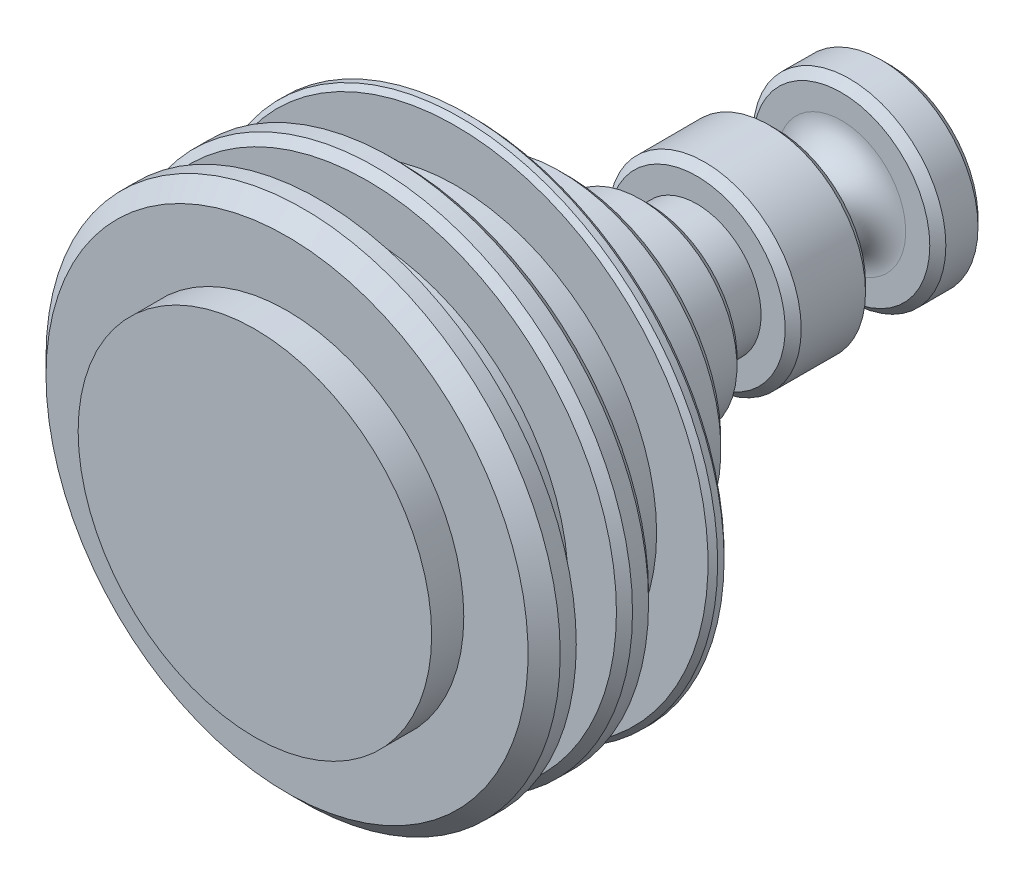
SolidWorks part; units mm, degrees
ref_plane "Plane1" through (0, 0, 0) normal (0, 0, 1) x (1, 0, 0)
ref_plane "Plane2" through (0, 0, 0) normal (0, 1, 0) x (1, 0, 0)
ref_plane "Plane3" through (0, 0, 0) normal (1, 0, 0) x (0, 0, -1)
sketch "Esquisse1" plane through (0, 0, 0) normal (0, 0, 1) x (1, 0, 0)
  circle A0 centre (0, 0) radius 11
  dimension "D1" = 22
extrude "fond" add sketch "Esquisse1" along normal blind 2
sketch "Esquisse2" plane through (0, 0, 0) normal (0, 0, -1) x (-1, 0, 0)
  circle A0 centre (0, 0) radius 16
  dimension "D1" = 32
extrude "cylindre 1" add sketch "Esquisse2" along normal blind 2
sketch "Esquisse3" plane through (0, 0, -2) normal (0, 0, -1) x (-1, 0, 0)
  circle A0 centre (0, 0) radius 12.5
  dimension "D1" = 25
extrude "cylindre 2" add sketch "Esquisse3" along normal blind 3
sketch "Esquisse4" plane through (0, 0, -5) normal (0, 0, -1) x (-1, 0, 0)
  circle A0 centre (0, 0) radius 16
  dimension "D1" = 32
extrude "cylindre 3" add sketch "Esquisse4" along normal blind 2
sketch "Esquisse5" plane through (0, 0, -7) normal (0, 0, -1) x (-1, 0, 0)
  circle A0 centre (0, 0) radius 12.5
  dimension "D1" = 25
extrude "cylindre 4" add sketch "Esquisse5" along normal blind 3.5
sketch "Esquisse6" plane through (0, 0, -10.5) normal (0, 0, -1) x (-1, 0, 0)
  circle A0 centre (0, 0) radius 16
  dimension "D1" = 32
extrude "cylindre 5" add sketch "Esquisse6" along normal blind 1
sketch "Esquisse7" plane through (0, 0, -11.5) normal (0, 0, -1) x (-1, 0, 0)
  circle A0 centre (0, 0) radius 10
  dimension "D1" = 20
extrude "cylindre 6" add sketch "Esquisse7" along normal blind 6
sketch "Esquisse8" plane through (0, 0, -17.5) normal (0, 0, -1) x (-1, 0, 0)
  circle A0 centre (0, 0) radius 6
  dimension "D1" = 12
extrude "cylindre 7" add sketch "Esquisse8" along normal blind 5
sketch "Esquisse9" plane through (0, 0, -22.5) normal (0, 0, -1) x (-1, 0, 0)
  circle A0 centre (0, 0) radius 4
  dimension "D1" = 8
extrude "cylindre 8" add sketch "Esquisse9" along normal blind 3
sketch "Esquisse12" plane through (0, 0, -25.5) normal (0, 0, -1) x (-1, 0, 0)
  circle A0 centre (0, 0) radius 6
  dimension "D1" = 12
extrude "cylindre 9" add sketch "Esquisse12" along normal blind 12
sketch "Esquisse13" plane through (0, 0, 0) normal (0, 1, 0) x (1, 0, 0)
  line L0 (-10.4858, 34.5) -> (-4, 34.5)
  line L1 (-10.4858, 30.5) -> (-4, 30.5)
  line L2 (-6, 25.5) -> (6, 25.5) construction
  line L3 (-6, 37.5) -> (-6, 25.5) construction
  line L5 (-10.4858, 30.5) -> (-10.4858, 34.5)
  arc A0 (-4, 34.5) -> (-4, 30.5) centre (-4, 32.5) cw
  dimension "D1" = 5
  dimension "D2" = 4
  dimension "D3" = 2
ref_plane "Plan1" through (0, 0, -32.5) normal (0, 0, 1) x (1, 0, 0)
sketch "Esquisse16" plane through (0, 0, -32.5) normal (0, 0, 1) x (1, 0, 0)
  circle A0 centre (0, 0) radius 2
  dimension "D1" = 4
sweep "gorge" cut profiles "Esquisse13" path "Esquisse16"
chamfer "Chanfrein1" distance 0.5 angle 45
chamfer "Chanfrein2" distance 0.3 angle 45
chamfer "Chanfrein3" distance 1 angle 45
